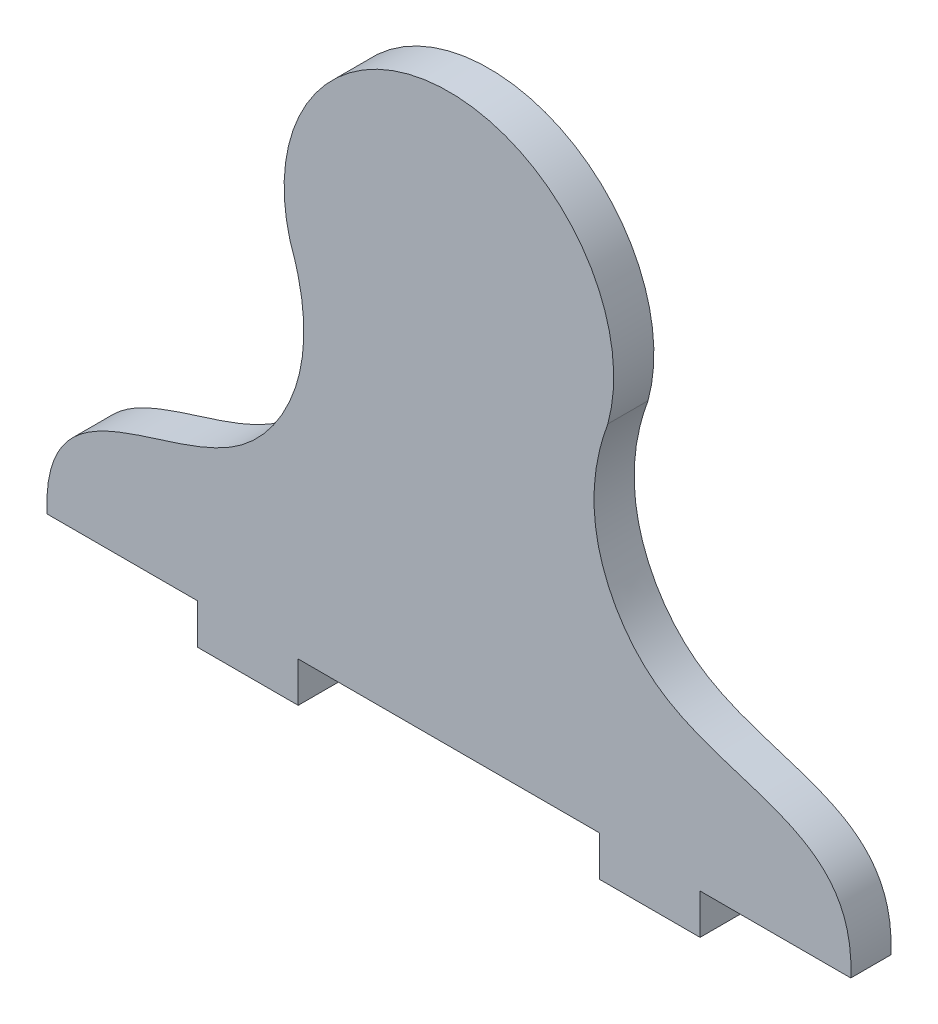
SolidWorks part; units mm, degrees
ref_plane "Front Plane" through (0, 0, 0) normal (0, 0, 1) x (1, 0, 0)
ref_plane "Top Plane" through (0, 0, 0) normal (0, 1, 0) x (1, 0, 0)
ref_plane "Right Plane" through (0, 0, 0) normal (1, 0, 0) x (0, 0, -1)
sketch "Sketch1" plane through (0, 0, 0) normal (0, 0, 1) x (1, 0, 0)
  line L0 (0, 0) -> (15, 0)
  line L1 (40, 0) -> (40, 62.6795) construction
  line L2 (25, 0) -> (55, 0)
  line L3 (65, 0) -> (65, -4)
  line L4 (25, 0) -> (25, -4)
  line L5 (25, -4) -> (15, -4)
  line L6 (15, 0) -> (15, -4)
  line L7 (55, -4) -> (65, -4)
  line L8 (55, 0) -> (55, -4)
  line L9 (80, 0) -> (65, 0)
  arc A0 (55.2576, 33.9824) -> (24.7424, 33.9824) centre (40, 40) ccw
  spline S0 degree 3 poles (0, 0) (-0.5582, 12.4299) (16.9175, 9.4008) (26.3378, 24.3931) (25.6267, 31.8045) (24.1807, 35.6692) knots 0 0 0 0 0.197688 0.274981 0.360749 0.360749 0.360749 0.360749
  spline S1 degree 3 poles (80, 0) (80.5582, 12.4299) (63.0825, 9.4008) (53.6622, 24.3931) (54.3733, 31.8045) (55.8193, 35.6692) knots 0 0 0 0 0.197688 0.274981 0.360749 0.360749 0.360749 0.360749
  dimension "D2" = 30
  dimension "D3" = 10
  dimension "D4" = 4
  dimension "D5" = 40
extrude "Boss-Extrude1" add sketch "Sketch1" along normal blind 4 contours L1 L2 L8 L7 L3 L9 S1 A0 | L2 L1 A0 S0 L0 L6 L5 L4
